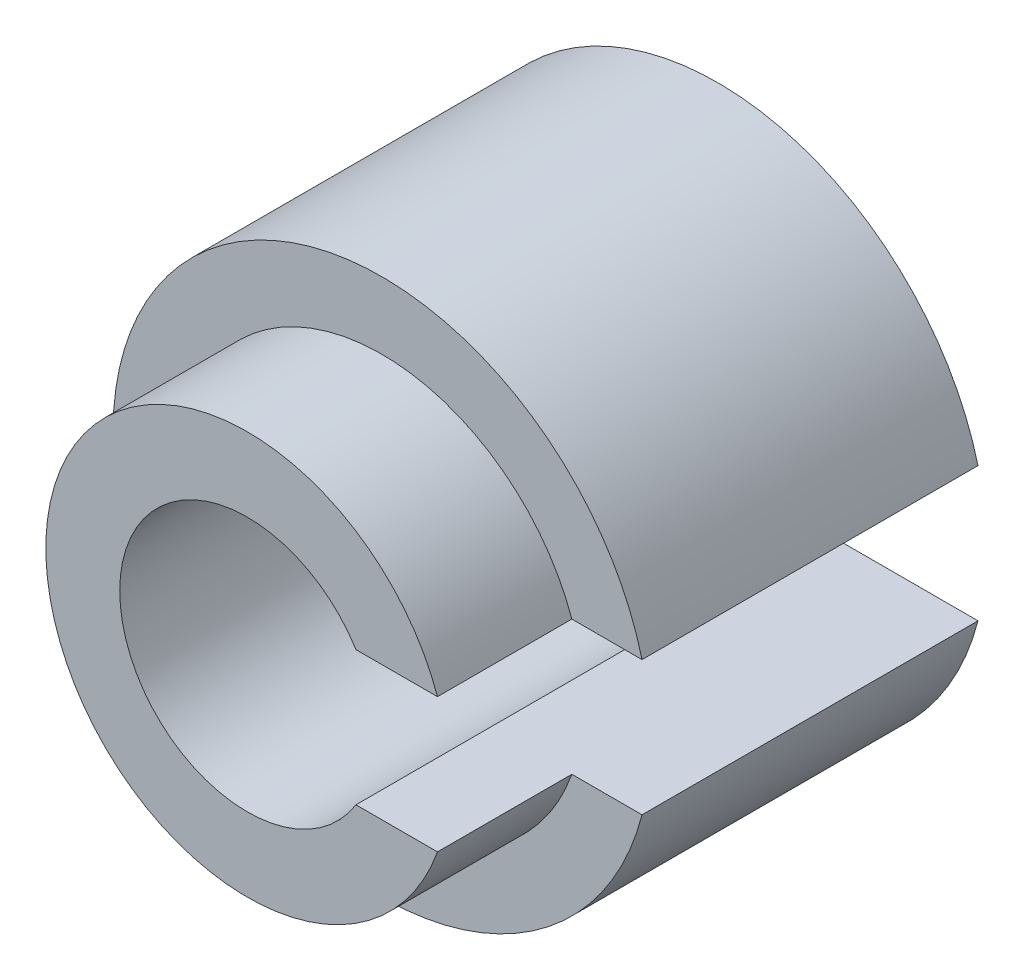
SolidWorks part; units mm, degrees
ref_plane "前视基准面" through (0, 0, 0) normal (0, 0, 1) x (1, 0, 0)
ref_plane "上视基准面" through (0, 0, 0) normal (0, 1, 0) x (1, 0, 0)
ref_plane "右视基准面" through (0, 0, 0) normal (1, 0, 0) x (0, 0, -1)
sketch "草图1" plane through (0, 0, 0) normal (0, 0, 1) x (1, 0, 0)
  circle A0 centre (0, 0) radius 4
  dimension "D1" = 8
extrude "凸台-拉伸1" add sketch "草图1" along normal blind 5
sketch "草图2" plane through (0, 0, 5) normal (0, 0, 1) x (1, 0, 0)
  circle A0 centre (0, 0) radius 3
  dimension "D1" = 6
extrude "凸台-拉伸2" add sketch "草图2" along normal blind 2
sketch "草图3" plane through (0, 0, 7) normal (0, 0, 1) x (1, 0, 0)
  circle A0 centre (0, 0) radius 1.9
  dimension "D1" = 3.8
extrude "切除-拉伸1" cut sketch "草图3" against normal through all
sketch "草图4" plane through (0, 0, 0) normal (0, 1, 0) x (1, 0, 0)
  line L0 (0, 0) -> (0, -8.8051) construction
  line L1 (0, 0) -> (4, 0)
  line L2 (4, 0) -> (4, -5)
  line L3 (4, -5) -> (3, -5)
  line L4 (3, -5) -> (3, -7)
  line L5 (3, -7) -> (0, -7)
  line L6 (0, -7) -> (0, 0)
  dimension "D1" = 4
  dimension "D2" = 5
extrude "切除-拉伸2" cut sketch "草图4" against normal mid plane 2
